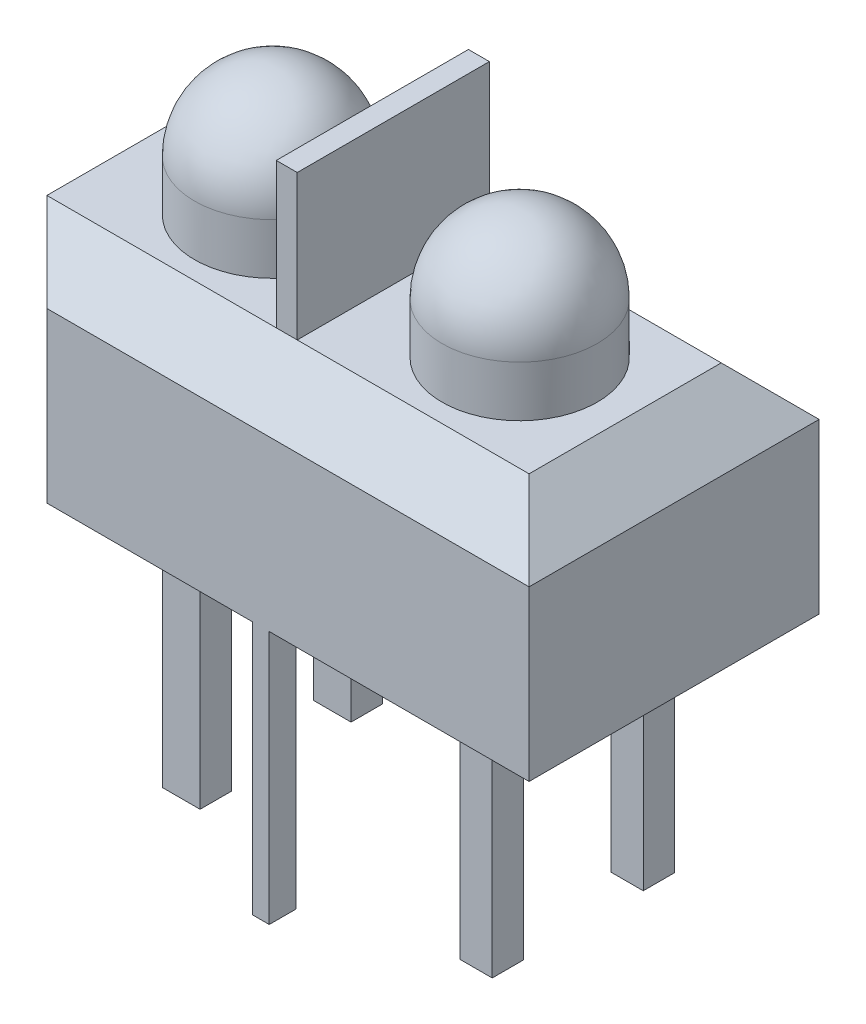
SolidWorks part; units mm, degrees
ref_plane "前视基准面" through (0, 0, 0) normal (0, 0, 1) x (1, 0, 0)
ref_plane "上视基准面" through (0, 0, 0) normal (0, 1, 0) x (1, 0, 0)
ref_plane "右视基准面" through (0, 0, 0) normal (1, 0, 0) x (0, 0, -1)
sketch "草图1" plane through (0, 0, 0) normal (0, 1, 0) x (1, 0, 0)
  line L1 (-4, -2) -> (4, -2)
  line L2 (-4, -2) -> (-4, 2)
  line L3 (-4, 2) -> (4, 2)
  line L4 (4, -2) -> (4, 2)
  line L5 (-4, -2) -> (4, 2) construction
  line L6 (-4, 2) -> (4, -2) construction
  point P0 (0, 0)
  dimension "D1" = 8
extrude "凸台-拉伸1" add sketch "草图1" along normal blind 3
sketch "草图2" plane through (-4, 0, 0) normal (-1, 0, 0) x (0, 0, 1)
  line L0 (-2, 2.325) -> (-1.325, 3)
  line L1 (-2, 3) -> (-2, 0) construction
  line L2 (-2, 3) -> (2, 3) construction
  line L3 (-1.325, 3) -> (-2, 3)
  line L4 (-2, 3) -> (-2, 2.325)
  line L5 (2, 2.325) -> (1.325, 3)
  line L6 (2, 3) -> (2, 0) construction
  line L7 (1.325, 3) -> (2, 3)
  line L8 (2, 3) -> (2, 2.325)
extrude "切除-拉伸1" cut sketch "草图2" against normal blind 10
sketch "草图3" plane through (0, 0, 2) normal (0, 0, 1) x (1, 0, 0)
  line L0 (-4, 2.325) -> (-3.325, 3)
  line L1 (-4, 3) -> (4, 3) construction
  line L2 (-3.325, 3) -> (-4, 3)
  line L3 (-4, 3) -> (-4, 2.325)
  line L4 (4, 2.325) -> (3.325, 3)
  line L6 (3.325, 3) -> (4, 3)
  line L7 (4, 3) -> (4, 2.325) construction
  line L8 (4, 3) -> (4, 2.325)
extrude "切除-拉伸2" cut sketch "草图3" against normal blind 10
sketch "草图4" plane through (0, 3, 0) normal (0, 1, 0) x (1, 0, 0)
  line L0 (-3.325, 1.325) -> (-2.65, 2)
  line L1 (4, 2) -> (-4, 2) construction
  line L2 (-2.65, 2) -> (-4, 2)
  line L3 (-3.325, 1.325) -> (-4, 0.65)
  line L4 (-4, 2) -> (-4, -2) construction
  line L5 (-4, 0.65) -> (-4, 2)
  line L6 (-3.325, -1.325) -> (-2.65, -2)
  line L7 (4, -2) -> (-4, -2) construction
  line L8 (-2.65, -2) -> (-4, -2)
  line L9 (-3.325, -1.325) -> (-4, -0.65)
  line L10 (-4, -0.65) -> (-4, -2)
extrude "切除-拉伸3" cut sketch "草图4" against normal blind 10
sketch "草图5" plane through (0, 3, 0) normal (0, 1, 0) x (1, 0, 0)
  line L0 (0.1275, 1.325) -> (0.1275, -1.325)
  line L1 (3.325, 1.325) -> (-3.325, 1.325) construction
  line L2 (-3.325, -1.325) -> (3.325, -1.325) construction
  line L3 (0.1275, -1.325) -> (-0.1615, -1.325)
  line L4 (-0.1615, -1.325) -> (-0.1615, 1.325)
  line L5 (-0.1615, 1.325) -> (0.1275, 1.325)
extrude "凸台-拉伸2" add sketch "草图5" along normal blind 2
sketch "草图6" plane through (0, 3, 0) normal (0, 1, 0) x (1, 0, 0)
  circle A0 centre (-1.5387, 0) radius 1.0748
extrude "凸台-拉伸3" add sketch "草图6" along normal blind 0.7
sketch "草图7" plane through (0, 3.7, 0) normal (0, 1, 0) x (1, 0, 0)
  line L0 (-0.4638, 0) -> (-2.6135, 0)
  arc A0 (-2.6135, 0) -> (-0.4638, 0) centre (-1.5387, 0) ccw
revolve "旋转1" add sketch "草图7" angle 360 about L0
sketch "草图8" plane through (0, 3, 0) normal (0, 1, 0) x (1, 0, 0)
  circle A0 centre (1.8702, 0) radius 1.07
extrude "凸台-拉伸4" add sketch "草图8" along normal blind 0.7
sketch "草图9" plane through (0, 3.7, 0) normal (0, 1, 0) x (1, 0, 0)
  line L1 (2.9357, 0) -> (2.9402, 0)
  line L2 (2.9357, 0) -> (2.9402, 0)
  circle A0 centre (1.8702, 0) radius 1.07 construction
sketch "草图12" plane through (0, 3.7, 0) normal (0, 1, 0) x (1, 0, 0)
  line L0 (0.8002, 0) -> (2.9402, 0)
  arc A0 (0.8002, 0) -> (2.9402, 0) centre (1.8702, 0) ccw
revolve "旋转2" add sketch "草图12" angle 360 about L0
sketch "草图13" plane through (0, 0, 0) normal (0, -1, 0) x (1, 0, 0)
  line L0 (-1.9552, 1.1009) -> (-1.9552, 0.6673)
  line L1 (-1.9552, 0.6673) -> (-1.4366, 0.6673)
  line L2 (-1.4366, 0.6673) -> (-1.4366, 1.1009)
  line L3 (-1.4366, 1.1009) -> (-1.9552, 1.1009)
  line L4 (-1.9552, -1.4154) -> (-1.9552, -0.9819)
  line L5 (-1.9552, -0.9819) -> (-1.4366, -0.9819)
  line L6 (-1.4366, -0.9819) -> (-1.4366, -1.4154)
  line L7 (-1.4366, -1.4154) -> (-1.9552, -1.4154)
  line L8 (2.1507, 1.1009) -> (2.1507, 0.6673)
  line L9 (2.1507, 0.6673) -> (2.5928, 0.6673)
  line L10 (2.5928, 0.6673) -> (2.5928, 1.1009)
  line L11 (2.5928, 1.1009) -> (2.1507, 1.1009)
  line L12 (2.1507, -0.9819) -> (2.5928, -0.9819)
  line L13 (2.5928, -0.9819) -> (2.5928, -1.4154)
  line L14 (2.5928, -1.4154) -> (2.1507, -1.4154)
  line L15 (2.1507, -1.4154) -> (2.1507, -0.9819)
extrude "凸台-拉伸5" add sketch "草图13" along normal blind 3.5
sketch "草图14" plane through (0, 0, 0) normal (0, -1, 0) x (1, 0, 0)
  line L0 (0.187, 2) -> (0.187, 1.6279)
  line L1 (-2.65, 2) -> (4, 2) construction
  line L2 (0.187, 1.6279) -> (0.4165, 1.6279)
  line L3 (0.4165, 1.6279) -> (0.4165, 1.9425)
  line L4 (0.4165, 1.9425) -> (0.4165, 2)
  line L5 (0.4165, 2) -> (0.187, 2)
  line L6 (0.187, -2) -> (0.187, -1.5854)
  line L7 (4, -2) -> (-2.65, -2) construction
  line L8 (0.187, -1.5854) -> (0.4165, -1.5854)
  line L9 (0.4165, -1.5854) -> (0.4165, -2)
  line L10 (0.4165, -2) -> (0.187, -2)
extrude "凸台-拉伸6" add sketch "草图14" along normal blind 3.5
